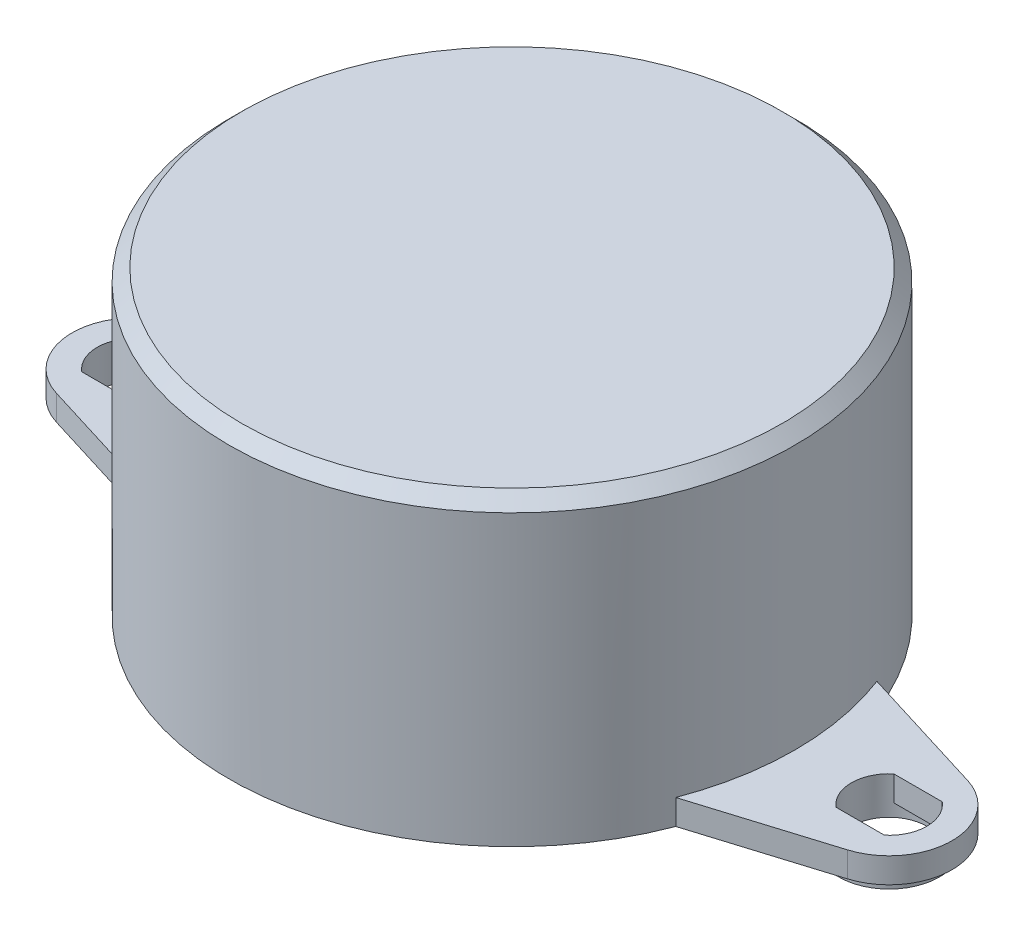
SolidWorks part; units mm, degrees
ref_plane "Front Plane" through (0, 0, 0) normal (0, 0, 1) x (1, 0, 0)
ref_plane "Top Plane" through (0, 0, 0) normal (0, 1, 0) x (1, 0, 0)
ref_plane "Right Plane" through (0, 0, 0) normal (1, 0, 0) x (0, 0, -1)
sketch "Sketch1" plane through (0, 0, 0) normal (0, 1, 0) x (1, 0, 0)
  circle A0 centre (0, 0) radius 11.25
  dimension "D1" = 22.5
extrude "Boss-Extrude1" add sketch "Sketch1" along normal blind 12
chamfer "Chamfer1" distance 0.5 angle 45 1 edges at (0, 12, 11.25)
sketch "Sketch2" plane through (0, 0, 0) normal (0, -1, 0) x (1, 0, 0)
  line L0 (-15.737, 2.3889) -> (-10.5149, 4)
  line L1 (-15.737, -2.3889) -> (-10.5149, -4)
  line L2 (15.737, -2.3889) -> (10.5149, -4)
  line L3 (15.737, 2.3889) -> (10.5149, 4)
  line L4 (-15, 0) -> (15, 0) construction
  line L5 (-17.5, -1000) -> (-17.5, 49000) construction
  line L6 (17.5, -1000) -> (17.5, 49000) construction
  line L7 (-15.9631, 1.15) -> (-14.0369, 1.15)
  line L8 (-14.0369, -1.15) -> (-15.9631, -1.15)
  line L9 (14.0369, 1.15) -> (15.9631, 1.15)
  line L10 (14.0369, -1.15) -> (15.9631, -1.15)
  arc A0 (-14.0369, -1.15) -> (-14.0369, 1.15) centre (-15, 0) ccw
  arc A1 (14.0369, 1.15) -> (14.0369, -1.15) centre (15, 0) ccw
  arc A2 (15.737, -2.3889) -> (15.737, 2.3889) centre (15, 0) ccw
  arc A3 (-15.737, 2.3889) -> (-15.737, -2.3889) centre (-15, 0) ccw
  circle A5 centre (0, 0) radius 11.25 construction
  arc A6 (10.5149, -4) -> (10.5149, 4) centre (0, 0) ccw
  circle A7 centre (0, 0) radius 11.25
  arc A8 (-10.5149, 4) -> (-10.5149, -4) centre (0, 0) ccw
  arc A9 (-15.9631, -1.15) -> (-14.0369, -1.15) centre (-15, 0) ccw construction
  arc A10 (-14.0369, 1.15) -> (-15.9631, 1.15) centre (-15, 0) ccw construction
  arc A11 (-15.9631, 1.15) -> (-15.9631, -1.15) centre (-15, 0) ccw
  arc A12 (15.9631, 1.15) -> (14.0369, 1.15) centre (15, 0) ccw construction
  arc A13 (14.0369, -1.15) -> (15.9631, -1.15) centre (15, 0) ccw construction
  arc A14 (15.9631, -1.15) -> (15.9631, 1.15) centre (15, 0) ccw
  point P1 (16.2555, 1.15)
  point P4 (0, 0)
  point P20 (-17.5, 0)
  point P23 (17.5, 0)
  point P31 (0, 0)
  point P32 (0, 0)
  point P33 (0, 0)
  dimension "D2" = 3
  dimension "D3" = 35
  dimension "D4" = 30
  dimension "D5" = 2.3
  dimension "D6" = 8
  dimension "D1" = 0
extrude "Boss-Extrude2" add sketch "Sketch2" against normal blind 1
sketch "Sketch3" plane through (0, 0, 0) normal (0, -1, 0) x (1, 0, 0)
  circle A0 centre (-15, 0) radius 1.5
  circle A1 centre (15, 0) radius 1.5
  circle A2 centre (15, 0) radius 2
  circle A3 centre (-15, 0) radius 2
  dimension "D1" = 0.5
extrude "Boss-Extrude3" add sketch "Sketch3" along normal blind 0.5
